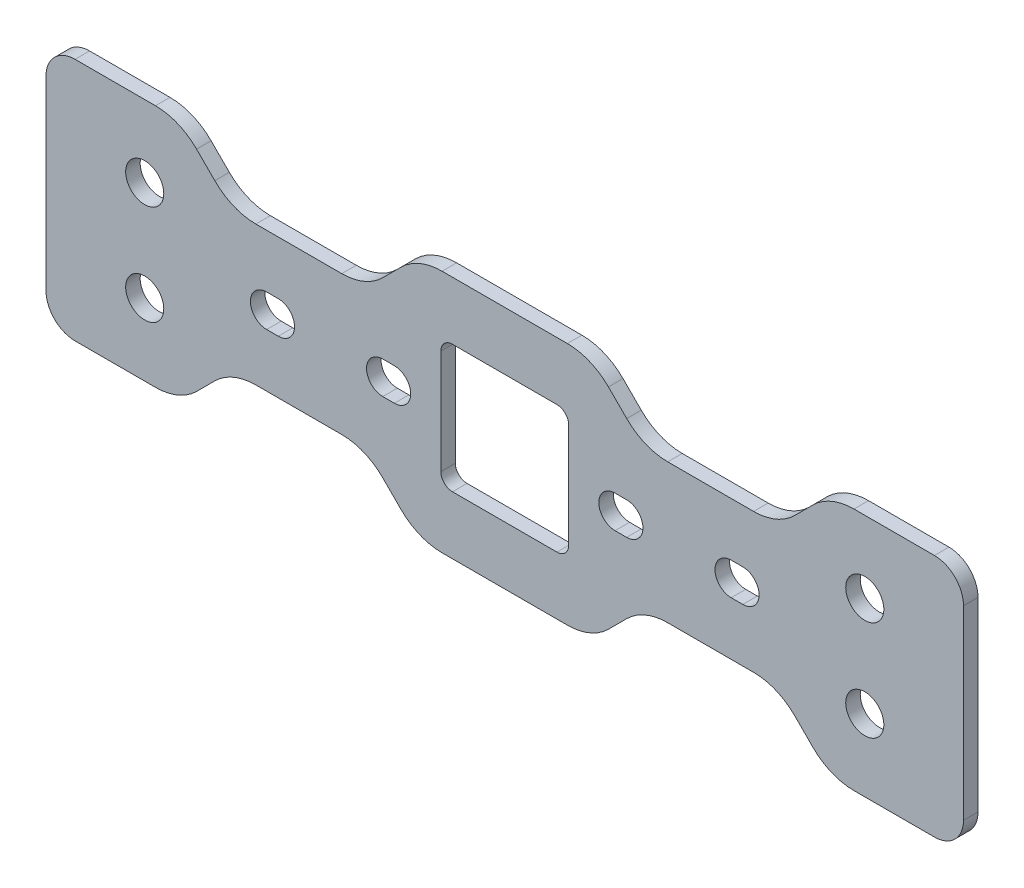
SolidWorks part; units mm, degrees
ref_plane "Front Plane" through (0, 0, 0) normal (0, 0, 1) x (1, 0, 0)
ref_plane "Top Plane" through (0, 0, 0) normal (0, 1, 0) x (1, 0, 0)
ref_plane "Right Plane" through (0, 0, 0) normal (1, 0, 0) x (0, 0, -1)
sketch "Sketch1" plane through (0, 0, 0) normal (0, 0, 1) x (1, 0, 0)
  line L0 (-100.33, -26.67) -> (100.33, 26.67) construction
  line L1 (-93.98, 26.67) -> (93.98, 26.67)
  line L2 (-100.33, 20.32) -> (-100.33, -20.32)
  line L3 (-93.98, -26.67) -> (93.98, -26.67)
  line L4 (100.33, 20.32) -> (100.33, -20.32)
  line L5 (-78.74, 10.922) -> (-78.74, -10.922) construction
  line L6 (-78.74, 0) -> (0, 0) construction
  line L7 (-97.79, -10.922) -> (-59.69, -10.922) construction
  line L8 (-13.97, 13.97) -> (13.97, -13.97) construction
  line L9 (-11.43, 13.97) -> (11.43, 13.97)
  line L10 (-13.97, 11.43) -> (-13.97, -11.43)
  line L11 (-11.43, -13.97) -> (11.43, -13.97)
  line L12 (13.97, 11.43) -> (13.97, -11.43)
  line L13 (0, 0) -> (0, 26.67) construction
  line L14 (-52.07, 0) -> (-49.53, 0) construction
  line L15 (-52.07, 3.556) -> (-49.53, 3.556)
  line L16 (-52.07, -3.556) -> (-49.53, -3.556)
  line L17 (-26.67, 0) -> (-24.13, 0) construction
  line L18 (-26.67, 3.556) -> (-24.13, 3.556)
  line L19 (-26.67, -3.556) -> (-24.13, -3.556)
  line L20 (26.67, 0) -> (24.13, 0) construction
  line L21 (26.67, 3.556) -> (24.13, 3.556)
  line L22 (26.67, -3.556) -> (24.13, -3.556)
  line L23 (52.07, 0) -> (49.53, 0) construction
  line L24 (52.07, 3.556) -> (49.53, 3.556)
  line L25 (52.07, -3.556) -> (49.53, -3.556)
  circle A0 centre (-78.74, 10.922) radius 4.1656
  circle A1 centre (-78.74, -10.922) radius 4.1656
  circle A2 centre (78.74, -10.922) radius 4.1656
  circle A3 centre (78.74, 10.922) radius 4.1656
  arc A4 (-11.43, -13.97) -> (-13.97, -11.43) centre (-11.43, -11.43) cw
  arc A5 (11.43, -13.97) -> (13.97, -11.43) centre (11.43, -11.43) ccw
  arc A6 (13.97, 11.43) -> (11.43, 13.97) centre (11.43, 11.43) ccw
  arc A7 (-11.43, 13.97) -> (-13.97, 11.43) centre (-11.43, 11.43) ccw
  arc A8 (100.33, 20.32) -> (93.98, 26.67) centre (93.98, 20.32) ccw
  arc A9 (93.98, -26.67) -> (100.33, -20.32) centre (93.98, -20.32) ccw
  arc A10 (-93.98, -26.67) -> (-100.33, -20.32) centre (-93.98, -20.32) cw
  arc A11 (-100.33, 20.32) -> (-93.98, 26.67) centre (-93.98, 20.32) cw
  arc A12 (-52.07, 3.556) -> (-52.07, -3.556) centre (-52.07, 0) ccw
  arc A13 (-49.53, -3.556) -> (-49.53, 3.556) centre (-49.53, 0) ccw
  arc A14 (26.67, 3.556) -> (26.67, -3.556) centre (26.67, 0) cw
  arc A15 (24.13, -3.556) -> (24.13, 3.556) centre (24.13, 0) cw
  arc A16 (-26.67, 3.556) -> (-26.67, -3.556) centre (-26.67, 0) ccw
  arc A17 (-24.13, -3.556) -> (-24.13, 3.556) centre (-24.13, 0) ccw
  arc A18 (52.07, 3.556) -> (52.07, -3.556) centre (52.07, 0) cw
  arc A19 (49.53, -3.556) -> (49.53, 3.556) centre (49.53, 0) cw
  point P0 (0, 0)
  point P25 (-13.97, -13.97)
  point P46 (-50.8, 0)
  point P50 (25.4, 0)
  point P57 (-25.4, 0)
  point P67 (50.8, 0)
  dimension "D1" = 8.3312
  dimension "D7" = 2.54
  dimension "D8" = 6.35
  dimension "D10" = 3.556
  dimension "D2" = 21.844
  dimension "D3" = 38.1
  dimension "D4" = 27.94
  dimension "D5" = 78.74
  dimension "D6" = 12.7
  dimension "D9" = 2.54
  dimension "D11" = 2.54
  dimension "D12" = 25.4
  dimension "D13" = 11.43
extrude "Boss-Extrude1" add sketch "Sketch1" along normal blind 3.175
sketch "Sketch3" plane through (0, 0, 0) normal (0, 0, 1) x (1, 0, 0)
  line L0 (-78.74, 10.922) -> (-71.12, 10.922) construction
  line L1 (-71.12, 26.67) -> (-63.4097, 18.9597)
  line L2 (-54.4295, 15.24) -> (-35.6503, 15.24)
  line L3 (-26.67, 18.9597) -> (-18.9597, 26.67)
  line L4 (0, 26.67) -> (0, 0) construction
  line L5 (-71.12, 26.67) -> (-18.9597, 26.67)
  line L6 (0, 0) -> (-100.33, 0) construction
  line L7 (-100.33, 20.32) -> (-100.33, -20.32) construction
  line L8 (-71.12, -26.67) -> (-18.9597, -26.67)
  line L9 (-26.67, -18.9597) -> (-18.9597, -26.67)
  line L10 (-54.4295, -15.24) -> (-35.6503, -15.24)
  line L11 (-71.12, -26.67) -> (-63.4097, -18.9597)
  line L12 (22.8149, 22.8149) -> (13.2261, 13.2261) construction
  line L13 (93.98, 26.67) -> (-93.98, 26.67) construction
  line L14 (-71.12, 10.922) -> (-71.12, 26.67) construction
  line L15 (71.12, 10.922) -> (71.12, 26.67) construction
  line L16 (78.74, 10.922) -> (71.12, 10.922) construction
  line L17 (-22.8149, 22.8149) -> (-13.2261, 13.2261) construction
  line L18 (71.12, -26.67) -> (63.4097, -18.9597)
  line L19 (54.4295, -15.24) -> (35.6503, -15.24)
  line L20 (26.67, -18.9597) -> (18.9597, -26.67)
  line L21 (71.12, -26.67) -> (18.9597, -26.67)
  line L22 (71.12, 26.67) -> (18.9597, 26.67)
  line L23 (26.67, 18.9597) -> (18.9597, 26.67)
  line L24 (54.4295, 15.24) -> (35.6503, 15.24)
  line L25 (71.12, 26.67) -> (63.4097, 18.9597)
  arc A0 (-11.43, 13.97) -> (-13.97, 11.43) centre (-11.43, 11.43) ccw construction
  arc A1 (-35.6503, 15.24) -> (-26.67, 18.9597) centre (-35.6503, 27.94) ccw
  arc A2 (-54.4295, 15.24) -> (-63.4097, 18.9597) centre (-54.4295, 27.94) cw
  arc A3 (-35.6503, -15.24) -> (-26.67, -18.9597) centre (-35.6503, -27.94) cw
  arc A4 (-54.4295, -15.24) -> (-63.4097, -18.9597) centre (-54.4295, -27.94) ccw
  arc A5 (54.4295, -15.24) -> (63.4097, -18.9597) centre (54.4295, -27.94) cw
  arc A6 (35.6503, -15.24) -> (26.67, -18.9597) centre (35.6503, -27.94) ccw
  arc A7 (54.4295, 15.24) -> (63.4097, 18.9597) centre (54.4295, 27.94) ccw
  arc A8 (35.6503, 15.24) -> (26.67, 18.9597) centre (35.6503, 27.94) cw
  dimension "D1" = 12.7
  dimension "D2" = 45
  dimension "D3" = 45
  dimension "D4" = 15.24
  dimension "D5" = 7.62
extrude "Cut-Extrude2" cut sketch "Sketch3" along normal through all
fillet "Fillet1" radius 12.7 8 edges at (-71.12, -26.67, 1.5875) (-18.9597, -26.67, 1.5875) (18.9597, -26.67, 1.5875) (71.12, -26.67, 1.5875) (71.12, 26.67, 1.5875) (18.9597, 26.67, 1.5875) (-18.9597, 26.67, 1.5875) (-71.12, 26.67, 1.5875)
